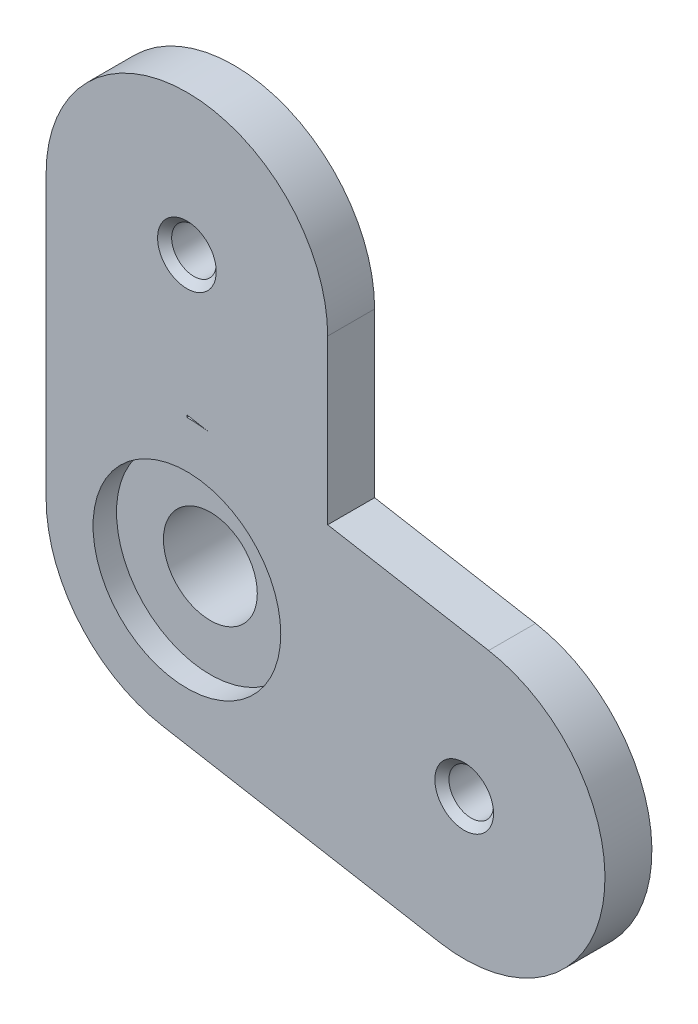
SolidWorks part; units mm, degrees
material "ABS PC"
ref_plane "前视基准面" through (0, 0, 0) normal (0, 0, 1) x (1, 0, 0)
ref_plane "上视基准面" through (0, 0, 0) normal (0, 1, 0) x (1, 0, 0)
ref_plane "右视基准面" through (0, 0, 0) normal (1, 0, 0) x (0, 0, -1)
sketch "草图1" plane through (0, 0, 0) normal (0, 0, 1) x (1, 0, 0)
  line L0 (5.3879, -3.9963) -> (-0.5209, -2.9544)
  line L1 (-3, 0) -> (3, 0)
  line L2 (-3, 0) -> (-3, 6)
  line L3 (-3, 6) -> (3, 6)
  line L4 (3, 0) -> (3, 6)
  line L5 (0, 3.0463) -> (6.4298, 1.9125)
  line L6 (0, 3.0463) -> (0, -3.0463)
  line L7 (0, -3.0463) -> (5.3879, -3.9963)
  line L8 (6.4298, 1.9125) -> (5.3879, -3.9963)
  circle A1 centre (0, 0) radius 3
  circle A2 centre (0, 6) radius 3
  circle A3 centre (5.9088, -1.0419) radius 3
  dimension "D1" = 6
  dimension "D2" = 6
  dimension "D3" = 6
  dimension "D5" = 6
  dimension "D6" = 100
extrude "凸台-拉伸1" add sketch "草图1" along normal blind 1 contours L1 A1 L6 | L6 A1 L1 | A3 A1 L7 | L8 A3 | L8 A3 | L3 A2 | A3 L5 L4 | L3 A2 | A2 L5 L4 | L6 A1 L1 | L1 A1 L6 | A2 L2 A1 | A1 L4 L5 | A1 L0 L6
sketch "草图2" plane through (0, 0, 0) normal (0, 0, -1) x (-1, 0, 0)
  circle A0 centre (0, 0) radius 2.5
  dimension "D1" = 5
extrude "凸台-拉伸2" add sketch "草图2" along normal blind 3
sketch "草图3" plane through (0, 0, -3) normal (0, 0, -1) x (-1, 0, 0)
  circle A0 centre (0, 0) radius 1
  dimension "D1" = 2
extrude "切除-拉伸1" cut sketch "草图3" against normal through all
sketch "草图4" plane through (0, 0, 1) normal (0, 0, 1) x (1, 0, 0)
  circle A0 centre (0, 0) radius 2
  dimension "D1" = 4
extrude "切除-拉伸2" cut sketch "草图4" against normal blind 0.5
sketch "草图5" plane through (0, 0, 0) normal (0, 1, 0) x (1, 0, 0)
  line L0 (-2.5, 3) -> (2.5, 0.1132)
  line L1 (2.5, 0) -> (2.5, 3) construction
  line L2 (2.5, 0.1132) -> (2.5, 3)
  line L3 (2.5, 3) -> (-2.5, 3) construction
  line L4 (2.5, 3) -> (-2.5, 3)
  dimension "D1" = 30
extrude "切除-拉伸3" cut sketch "草图5" against normal through all both and the other way through all
sketch "草图6" plane through (0, 0, 1) normal (0, 0, 1) x (1, 0, 0)
  circle A0 centre (0, 6) radius 1.5
  circle A1 centre (5.9088, -1.0419) radius 1.5
  dimension "D1" = 3
  dimension "D2" = 3
hole_wizard "M1.2x0.25 螺纹孔1" positions "草图7" profile "草图8" tap size "M1.2x0.25" standard "GB" end condition through all
sketch "草图7" plane through (0, 0, 1) normal (0, 0, 1) x (1, 0, 0)
  point P0 (0, 6)
  point P3 (5.9088, -1.0419)
sketch "草图8" plane through (0, 6, 1) normal (1, 0, 0) x (0, -1, 0)
  line L0 (0, 0) -> (0, 4)
  line L1 (0, 4) -> (0.475, 4)
  line L2 (0.475, 4) -> (0.475, 0.15)
  line L3 (0.475, 0.15) -> (0.625, 0)
  line L5 (0.625, 0) -> (0, 0)
  line L6 (-0.475, 0.15) -> (-0.625, 0) construction
  line L11 (0, -6.35) -> (0, 107.95) construction
  dimension "通孔螺纹孔钻头直径" = 0.95
  dimension "通孔螺纹孔钻头深度" = 4
  dimension "近端锥形沉头孔直径" = 1.25
  dimension "近端锥形沉头孔角度" = 90
cosmetic thread "孔螺蚊线1" parameters "D2"=1.2
cosmetic thread "孔螺蚊线2" parameters "D2"=1.2
